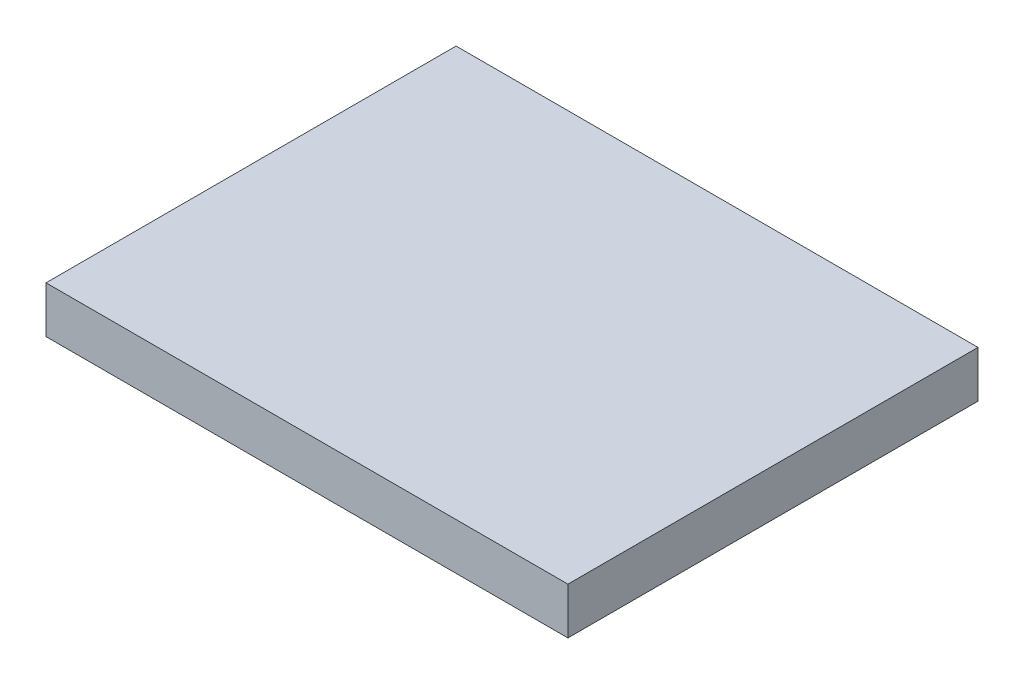
SolidWorks part; units mm, degrees
ref_plane "Front Plane" through (0, 0, 0) normal (0, 0, 1) x (1, 0, 0)
ref_plane "Top Plane" through (0, 0, 0) normal (0, 1, 0) x (1, 0, 0)
ref_plane "Right Plane" through (0, 0, 0) normal (1, 0, 0) x (0, 0, -1)
sketch "Sketch1" plane through (0, 0, 0) normal (0, 1, 0) x (1, 0, 0)
  line L1 (0, 0) -> (17.78, 0)
  line L2 (0, 0) -> (0, 13.97)
  line L3 (0, 13.97) -> (17.78, 13.97)
  line L4 (17.78, 0) -> (17.78, 13.97)
  dimension "D1" = 13.97
  dimension "D2" = 17.78
extrude "Boss-Extrude1" add sketch "Sketch1" along normal blind 1.5875
